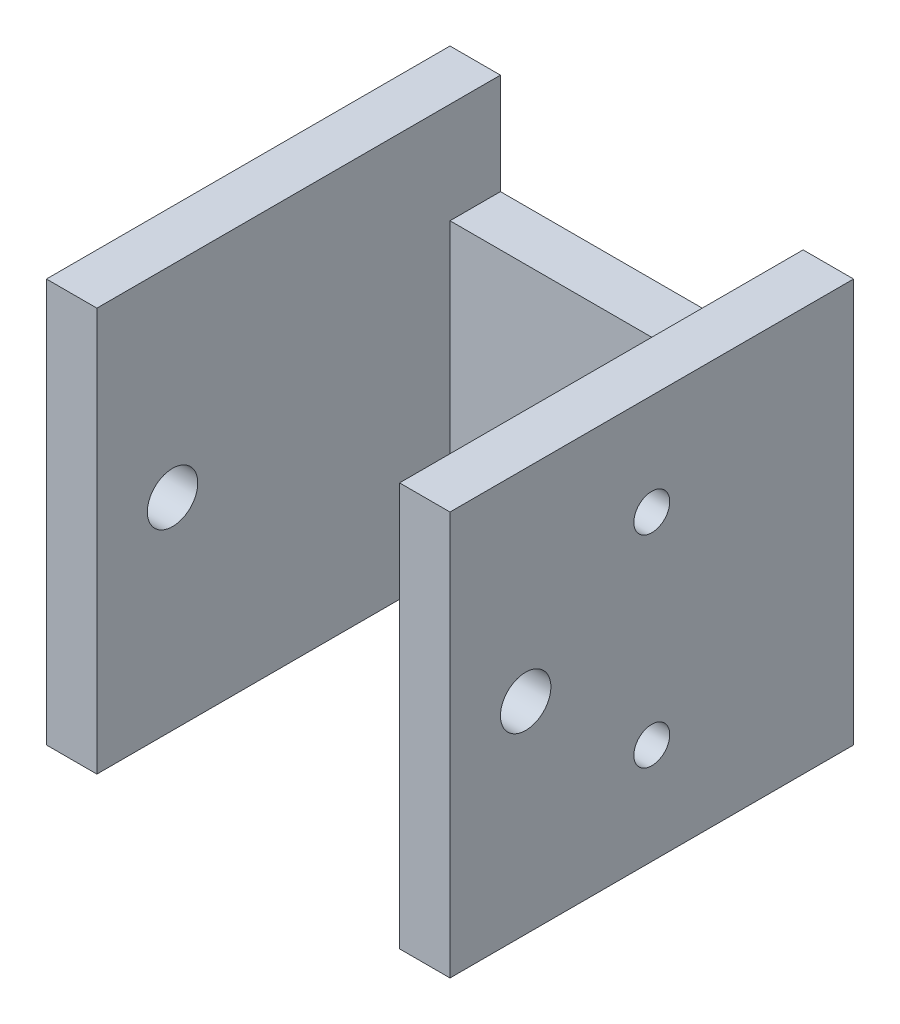
SolidWorks part; units mm, degrees
material "6061 Alloy"
ref_plane "Front Plane" through (0, 0, 0) normal (0, 0, 1) x (1, 0, 0)
ref_plane "Top Plane" through (0, 0, 0) normal (0, 1, 0) x (1, 0, 0)
ref_plane "Right Plane" through (0, 0, 0) normal (1, 0, 0) x (0, 0, -1)
sketch "Sketch1" plane through (0, 0, 0) normal (0, 1, 0) x (1, 0, 0)
  line L0 (0, 0) -> (0, 25.4)
  line L1 (0, 25.4) -> (25.4, 25.4)
  line L2 (25.4, 25.4) -> (25.4, 0)
  line L3 (25.4, 0) -> (22.225, 0)
  line L4 (22.225, 0) -> (22.225, 22.225)
  line L5 (22.225, 22.225) -> (3.175, 22.225)
  line L6 (3.175, 22.225) -> (3.175, 0)
  line L7 (3.175, 0) -> (0, 0)
  dimension "D1" = 25.4
  dimension "D2" = 25.4
  dimension "D3" = 3.175
  dimension "D4" = 3.175
  dimension "D5" = 3.175
extrude "Boss-Extrude1" add sketch "Sketch1" along normal blind 25.4
hole_wizard "1/8 (0.125) Diameter Hole1" positions "Sketch3" profile "Sketch2" hole size "1/8" standard "ANSI Inch" end condition through all
sketch "Sketch3" plane through (0, 0, 0) normal (-1, 0, 0) x (0, 0, 1)
  line L0 (0, 25.4) -> (0, 0) construction
  line L1 (-25.4, 0) -> (0, 0) construction
  point P0 (-4.7625, 12.7)
  dimension "D1" = 4.7625
  dimension "D2" = 12.7
sketch "Sketch2" plane through (0, 12.7, -4.7625) normal (0, 1, 0) x (0, 0, 1)
  line L0 (0, 0) -> (0, 25.4)
  line L1 (0, 25.4) -> (1.5875, 25.4)
  line L2 (1.5875, 25.4) -> (1.5875, 0)
  line L5 (1.5875, 0) -> (0, 0)
  line L11 (0, -6.35) -> (0, 107.95) construction
  dimension "Thru Hole Dia." = 3.175
  dimension "Thru Hole Depth" = 25.4
hole_wizard "#43 (0.089) Diameter Hole2" positions "Sketch7" profile "Sketch6" hole size "#43" standard "ANSI Inch"
sketch "Sketch7" plane through (25.4, 0, 0) normal (1, 0, 0) x (0, 0, -1)
  line L3 (25.4, 25.4) -> (25.4, 0) construction
  line L4 (0, 0) -> (25.4, 0) construction
  line L5 (0, 25.4) -> (25.4, 25.4) construction
  point P0 (12.7, 19.05)
  point P2 (12.7, 6.35)
  dimension "D1" = 6.35
  dimension "D2" = 6.35
  dimension "D3" = 12.7
  dimension "D4" = 12.7
sketch "Sketch6" plane through (25.4, 19.05, -12.7) normal (0, 1, 0) x (0, 0, -1)
  line L0 (0, 0) -> (0, 3.175)
  line L1 (0, 3.175) -> (1.1303, 3.175)
  line L2 (1.1303, 3.175) -> (1.1303, 0)
  line L5 (1.1303, 0) -> (0, 0)
  line L11 (0, -6.35) -> (0, 107.95) construction
  dimension "Thru Hole Dia." = 2.2606
  dimension "Thru Hole Depth" = 3.175
sketch "Sketch8" plane through (0, 0, -22.225) normal (0, 0, 1) x (1, 0, 0)
  line L0 (22.225, 25.4) -> (22.225, 0) construction
  line L1 (3.175, 25.4) -> (22.225, 25.4)
  line L2 (3.175, 25.4) -> (3.175, 19.05)
  line L3 (3.175, 19.05) -> (22.225, 19.05)
  line L4 (22.225, 25.4) -> (22.225, 19.05)
  line L6 (3.175, 0) -> (22.225, 0)
  line L7 (3.175, 0) -> (3.175, 6.35)
  line L8 (3.175, 6.35) -> (22.225, 6.35)
  line L9 (22.225, 0) -> (22.225, 6.35)
  dimension "D1" = 6.35
  dimension "D2" = 6.35
extrude "Cut-Extrude1" cut sketch "Sketch8" against normal up to next
